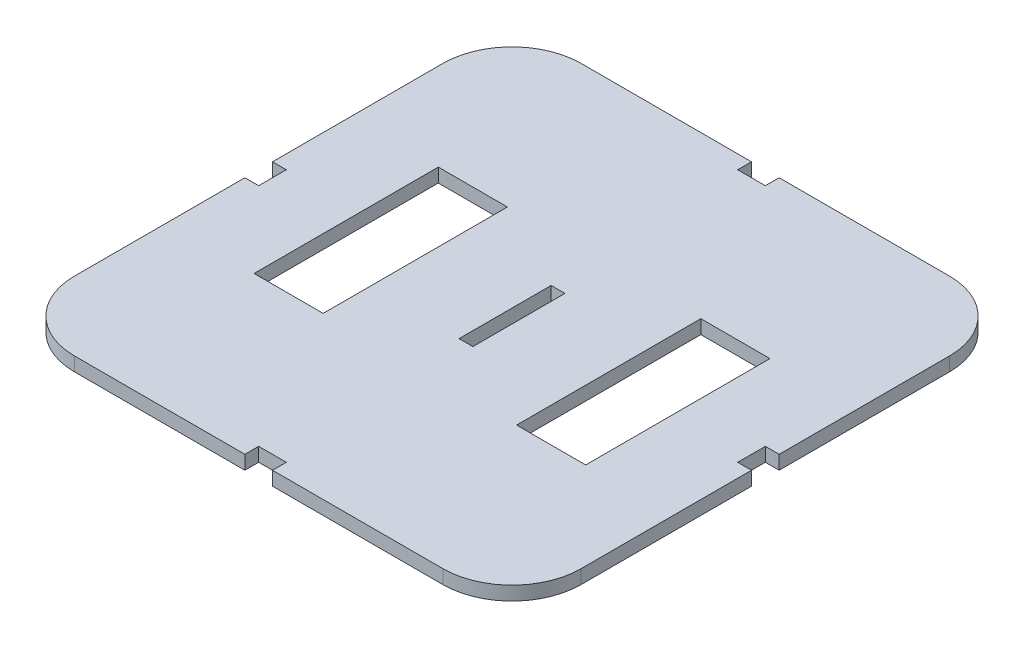
SolidWorks part; units mm, degrees
ref_plane "Спереди" through (0, 0, 0) normal (0, 0, 1) x (1, 0, 0)
ref_plane "Сверху" through (0, 0, 0) normal (0, 1, 0) x (1, 0, 0)
ref_plane "Справа" through (0, 0, 0) normal (1, 0, 0) x (0, 0, -1)
other "Configuration Table"
sketch "Эскиз4" plane through (0, 0, 0) normal (0, 1, 0) x (1, 0, 0)
  line L1 (0, 0) -> (110, 0)
  line L2 (0, 0) -> (0, 110)
  line L3 (0, 110) -> (110, 110)
  line L4 (110, 0) -> (110, 110)
  line L5 (107, 58) -> (110, 58)
  line L6 (55, 107) -> (52, 107)
  line L7 (52, 107) -> (55, 107)
  line L8 (55, 107) -> (58, 107)
  line L9 (52, 107) -> (52, 110)
  line L10 (58, 107) -> (58, 110)
  line L11 (58, 3) -> (58, 0)
  line L12 (55, 3) -> (58, 3)
  line L13 (55, 3) -> (52, 3)
  line L14 (52, 3) -> (52, 0)
  line L15 (3, 55) -> (3, 58)
  line L16 (3, 55) -> (3, 52)
  line L17 (3, 58) -> (0, 58)
  line L18 (3, 52) -> (0, 52)
  line L19 (107, 55) -> (107, 58)
  line L20 (107, 55) -> (107, 52)
  line L21 (107, 52) -> (110, 52)
  dimension "D3" = 3
extrude "Бобышка-Вытянуть3" add sketch "Эскиз4" along normal blind 3 contours L21 L20 L19 L5 L4 L3 L10 L8 L6 L9 L2 L17 L15 L16 L18 L1 L14 L13 L12 L11
fillet "Fillet1" radius 15 4 edges at (0, 1.5, -110) (0, 1.5, 0) (110, 1.5, -110) (110, 1.5, 0)
sketch "Sketch1" plane through (0, 3, 0) normal (0, 1, 0) x (1, 0, 0)
  line L0 (3, 52) -> (3, 58) construction
  line L13 (3, 55) -> (107, 55) construction
  line L14 (107, 58) -> (107, 52) construction
  line L15 (55, 107) -> (55, 3) construction
  line L16 (52, 107) -> (58, 107) construction
  line L17 (58, 3) -> (52, 3) construction
  line L19 (19, 75) -> (34, 75)
  line L20 (19, 75) -> (19, 35)
  line L21 (19, 35) -> (34, 35)
  line L22 (34, 75) -> (34, 35)
  line L23 (53.5, 65) -> (56.5, 65)
  line L24 (53.5, 65) -> (53.5, 45)
  line L25 (53.5, 45) -> (56.5, 45)
  line L26 (56.5, 65) -> (56.5, 45)
  line L27 (76, 75) -> (91, 75)
  line L28 (76, 75) -> (76, 35)
  line L29 (76, 35) -> (91, 35)
  line L30 (91, 75) -> (91, 35)
  point P18 (0, 0)
  point P19 (0, 0)
  point P20 (0, 0)
  point P21 (0, 0)
  point P22 (0, 0)
  point P29 (0, 0)
  point P30 (0, 0)
  dimension "D1" = 3
  dimension "D2" = 20
  dimension "D3" = 16
  dimension "D4" = 15
  dimension "D5" = 40
extrude "Cut-Extrude1" cut sketch "Sketch1" against normal blind 10
